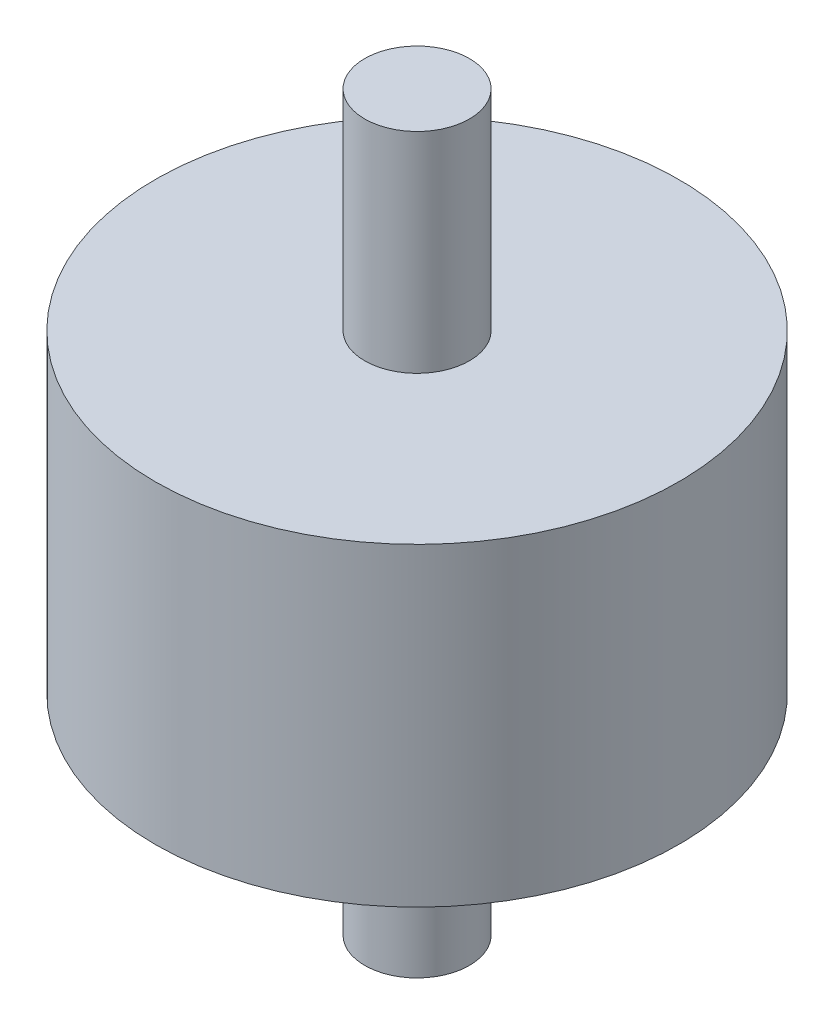
SolidWorks part; units mm, degrees
ref_plane "Front Plane" through (0, 0, 0) normal (0, 0, 1) x (1, 0, 0)
ref_plane "Top Plane" through (0, 0, 0) normal (0, 1, 0) x (1, 0, 0)
ref_plane "Right Plane" through (0, 0, 0) normal (1, 0, 0) x (0, 0, -1)
sketch "Sketch1" plane through (0, 0, 0) normal (0, 1, 0) x (1, 0, 0)
  circle A0 centre (0, 0) radius 2.5
  dimension "D1" = 5
extrude "Boss-Extrude1" add sketch "Sketch1" along normal blind 3
sketch "Sketch2" plane through (0, 3, 0) normal (0, 1, 0) x (1, 0, 0)
  circle A0 centre (0, 0) radius 0.5
  dimension "D1" = 1
extrude "Boss-Extrude2" add sketch "Sketch2" along normal blind 2
sketch "Sketch3" plane through (0, 0, 0) normal (0, -1, 0) x (-1, 0, 0)
  circle A0 centre (0, 0) radius 0.5
  dimension "D1" = 1
extrude "Boss-Extrude3" add sketch "Sketch3" along normal blind 2
